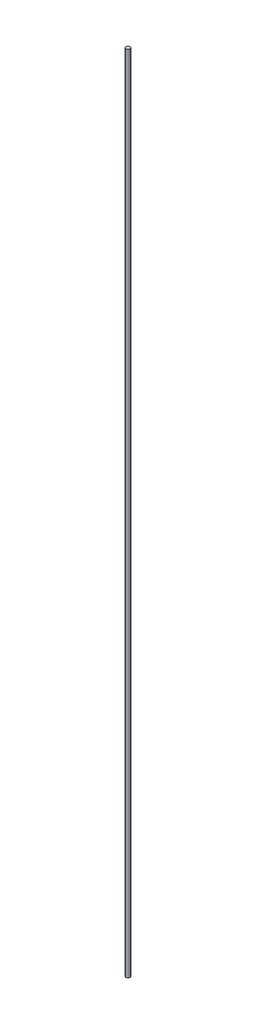
SolidWorks part; units mm, degrees
ref_plane "Front Plane" through (0, 0, 0) normal (0, 0, 1) x (1, 0, 0)
ref_plane "Top Plane" through (0, 0, 0) normal (0, 1, 0) x (1, 0, 0)
ref_plane "Right Plane" through (0, 0, 0) normal (1, 0, 0) x (0, 0, -1)
sketch "Sketch1" plane through (0, 0, 0) normal (0, 1, 0) x (1, 0, 0)
  circle A0 centre (0, 0) radius 0.75
  dimension "D1" = 1.5
extrude "Boss-Extrude1" add sketch "Sketch1" along normal blind 300
